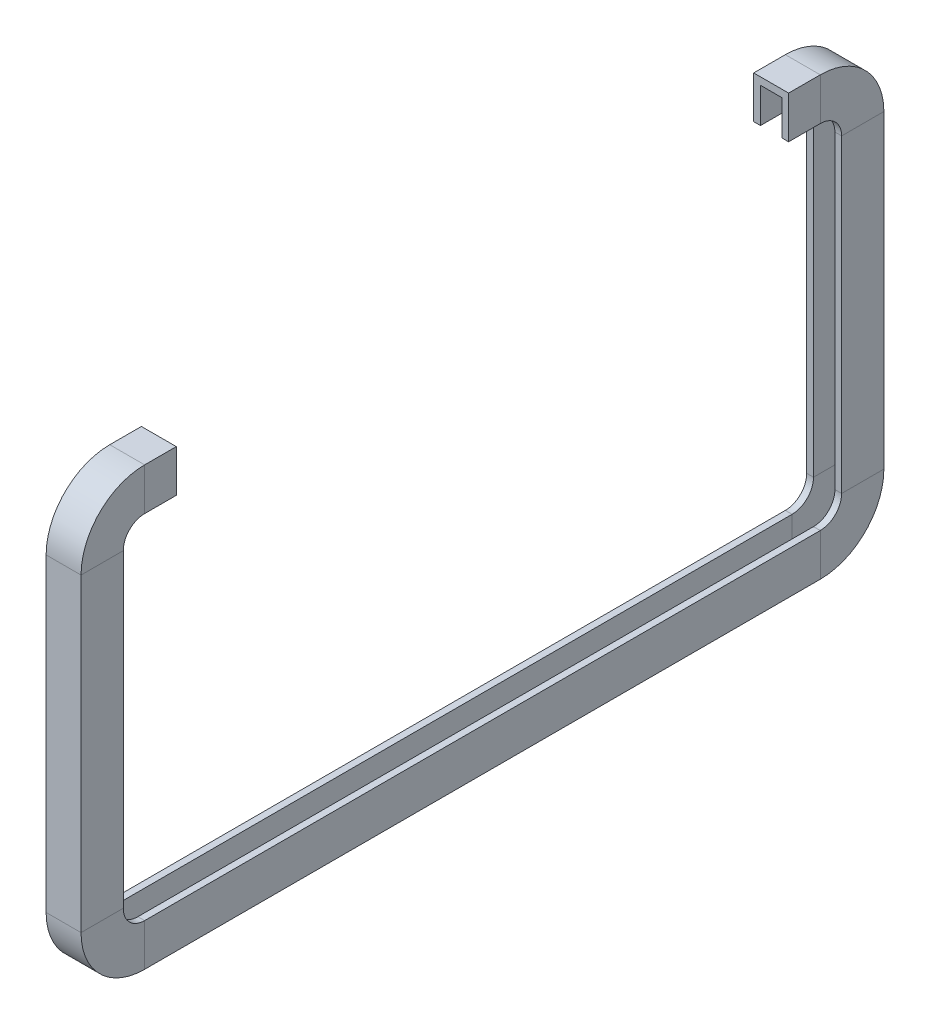
SolidWorks part; units mm, degrees
ref_plane "Front Plane" through (0, 0, 0) normal (0, 0, 1) x (1, 0, 0)
ref_plane "Top Plane" through (0, 0, 0) normal (0, 1, 0) x (1, 0, 0)
ref_plane "Right Plane" through (0, 0, 0) normal (1, 0, 0) x (0, 0, -1)
sketch "Sketch2" plane through (0, 0, 0) normal (0, 0, 1) x (1, 0, 0)
  line L0 (0, 0) -> (4.826, 0)
  line L1 (4.826, 0) -> (4.826, -7.874)
  line L2 (4.826, -7.874) -> (6.35, -7.874)
  line L3 (6.35, -7.874) -> (6.35, 1.651)
  line L5 (-1.524, 1.651) -> (-1.524, -7.874)
  line L6 (-1.524, -7.874) -> (0, -7.874)
  line L7 (0, -7.874) -> (0, 0)
  line L8 (-1.524, 1.651) -> (6.35, 1.651)
  dimension "D1" = 4.826
  dimension "D2" = 9.525
  dimension "D3" = 7.874
  dimension "D4" = 7.874
sketch "Sketch3" plane through (0, 0, 0) normal (1, 0, 0) x (0, 0, -1)
  line L0 (0, 0) -> (-7.1374, 0)
  line L1 (-19.8374, -12.7) -> (-19.8374, -82.55)
  line L2 (-7.1374, -95.25) -> (145.2626, -95.25)
  line L3 (157.9626, -82.55) -> (157.9626, -12.7)
  line L4 (145.2626, 0) -> (138.1252, 0)
  arc A0 (-19.8374, -12.7) -> (-7.1374, 0) centre (-7.1374, -12.7) cw
  arc A1 (-7.1374, -95.25) -> (-19.8374, -82.55) centre (-7.1374, -82.55) cw
  arc A2 (157.9626, -82.55) -> (145.2626, -95.25) centre (145.2626, -82.55) cw
  arc A3 (145.2626, 0) -> (157.9626, -12.7) centre (145.2626, -12.7) cw
  point P9 (-19.8374, 0)
  dimension "D2" = 12.7
  dimension "D1" = 19.8374
  dimension "D6" = 177.8
  dimension "D7" = 95.25
sweep "Sweep3" add profiles "Sketch2" path "Sketch3"
